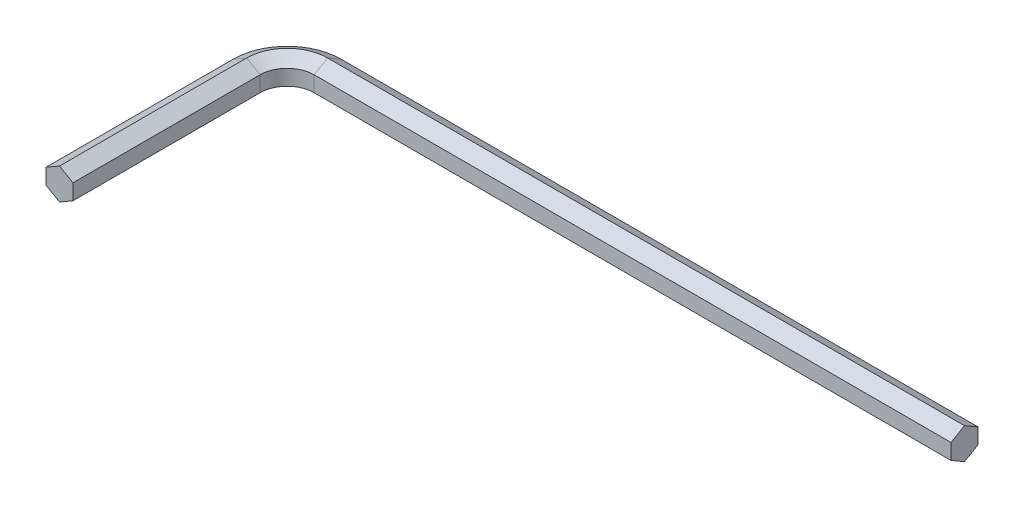
SolidWorks part; units mm, degrees
ref_plane "Front Plane" through (0, 0, 0) normal (0, 0, 1) x (1, 0, 0)
ref_plane "Top Plane" through (0, 0, 0) normal (0, 1, 0) x (1, 0, 0)
ref_plane "Right Plane" through (0, 0, 0) normal (1, 0, 0) x (0, 0, -1)
sketch "Sketch1" plane through (0, 0, 0) normal (0, 1, 0) x (1, 0, 0)
  line L0 (0, 0) -> (-47.2125, 0)
  line L1 (-49.2125, -2) -> (-49.2125, -15.875)
  arc A0 (-47.2125, 0) -> (-49.2125, -2) centre (-47.2125, -2) ccw
  point P6 (-49.2125, 0)
  dimension "D3" = 2
  dimension "D1" = 49.2125
  dimension "D2" = 15.875
sketch "Sketch2" plane through (0, 0, 0) normal (1, 0, 0) x (0, 0, -1)
  line L1 (1, -0.5774) -> (2, 0)
  line L2 (2, 0) -> (2, 1.1547)
  line L3 (2, 1.1547) -> (1, 1.7321)
  line L4 (1, 1.7321) -> (0, 1.1547)
  line L5 (0, 1.1547) -> (0, 0)
  line L6 (0, 0) -> (1, -0.5774)
  circle A0 centre (1, 0.5774) radius 1 construction
  dimension "D1" = 2
sweep "Sweep1" add profiles "Sketch2" path "Sketch1"
